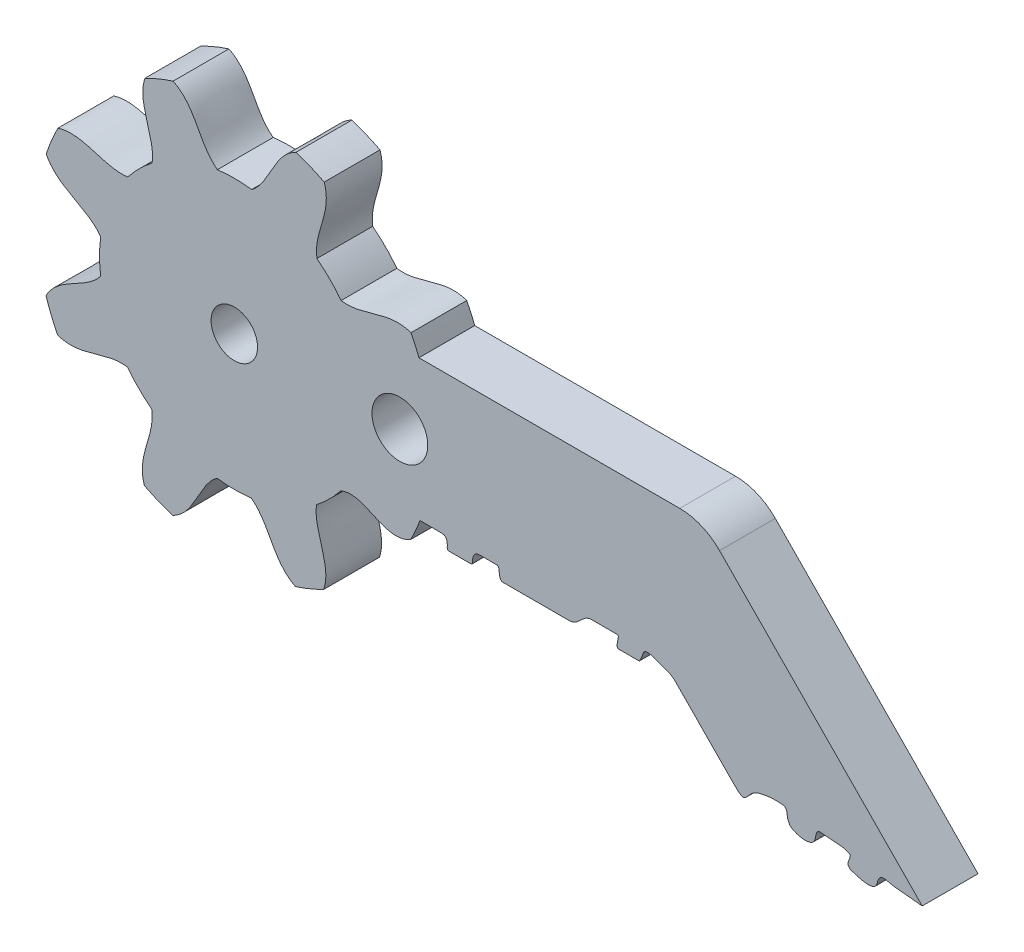
SolidWorks part; units mm, degrees
ref_plane "Plan de face" through (0, 0, 0) normal (0, 0, 1) x (1, 0, 0)
ref_plane "Plan de dessus" through (0, 0, 0) normal (0, 1, 0) x (1, 0, 0)
ref_plane "Plan de droite" through (0, 0, 0) normal (1, 0, 0) x (0, 0, -1)
sketch "Esquisse1" plane through (0, 0, 0) normal (0, 0, 1) x (1, 0, 0)
  line L0 (0.0131, -13.2918) -> (47.0131, -13.2918) construction
  line L1 (0, 0) -> (47, 0) construction
  line L2 (0, 0) -> (0, -20.3) construction
  line L3 (0, -20.3) -> (47, -20.3) construction
  line L4 (47, 0) -> (47, -20.3) construction
  line L5 (0, -10.15) -> (47, -10.15) construction
  line L6 (19.9298, -6.3) -> (35.218, -6.3)
  line L7 (47, -18.3) -> (35.218, -6.3)
  line L8 (10, -10.15) -> (5.9398, -0.3043) construction
  line L9 (33.7315, -14.492) -> (37.5973, -18.4293) construction
  line L10 (21.5121, -14.5) -> (22.7443, -14.5)
  line L11 (30.5976, -13.853) -> (29.2237, -13.853)
  line L12 (20.9504, -13.853) -> (19.9855, -13.853)
  line L13 (24.1135, -13.853) -> (23.1796, -13.853)
  line L14 (30.6788, -14.5) -> (31.7806, -14.5)
  line L15 (24.4805, -14.5) -> (28.0118, -14.5)
  line L16 (37.5973, -18.4293) -> (47, -18.3) construction
  line L17 (38.2306, -17.4342) -> (47, -18.3) construction
  line L18 (33.7315, -14.492) -> (36.7849, -17.6019)
  line L19 (45.6312, -18.1649) -> (47, -18.3)
  circle A0 centre (10, -10.15) radius 1.25
  circle A1 centre (18.7, -10.15) radius 1.25 construction
  circle A2 centre (10, -10.15) radius 7.25 construction
  circle A3 centre (10, -10.15) radius 10.65 construction
  arc A4 (5.1933, -0.6464) -> (6.7104, -0.0208) centre (10, -10.15) cw
  arc A5 (5.5762, -4.4061) -> (9.089, -2.9575) centre (10, -10.15) cw construction
  arc A6 (10.9334, -2.9603) -> (14.4417, -4.4199) centre (10, -10.15) cw construction
  arc A7 (13.3212, -0.0311) -> (14.8364, -0.6615) centre (10, -10.15) cw
  arc A8 (15.7439, -5.7262) -> (17.1925, -9.239) centre (10, -10.15) cw construction
  arc A9 (19.5036, -5.3433) -> (20.1292, -6.8604) centre (10, -10.15) cw construction
  arc A10 (17.1897, -11.0834) -> (15.7301, -14.5917) centre (10, -10.15) cw construction
  arc A11 (20.1189, -13.4712) -> (19.4885, -14.9864) centre (10, -10.15) cw construction
  arc A12 (14.4238, -15.8939) -> (10.911, -17.3425) centre (10, -10.15) cw construction
  arc A13 (14.8067, -19.6536) -> (13.2896, -20.2792) centre (10, -10.15) cw
  arc A14 (9.0666, -17.3397) -> (5.5583, -15.8801) centre (10, -10.15) cw construction
  arc A15 (6.6788, -20.2689) -> (5.1636, -19.6385) centre (10, -10.15) cw
  arc A16 (4.2561, -14.5738) -> (2.8075, -11.061) centre (10, -10.15) cw construction
  arc A17 (0.4964, -14.9567) -> (-0.1292, -13.4396) centre (10, -10.15) cw
  arc A18 (2.8103, -9.2166) -> (4.2699, -5.7083) centre (10, -10.15) cw construction
  arc A19 (-0.1189, -6.8288) -> (0.5115, -5.3136) centre (10, -10.15) cw
  arc A20 (5.5762, -4.4061) -> (4.2699, -5.7083) centre (10, -10.15) ccw
  arc A21 (2.8103, -9.2166) -> (2.8075, -11.061) centre (10, -10.15) ccw
  arc A22 (5.5583, -15.8801) -> (4.2561, -14.5738) centre (10, -10.15) cw
  arc A23 (9.0666, -17.3397) -> (10.911, -17.3425) centre (10, -10.15) ccw
  arc A24 (14.4238, -15.8939) -> (15.7301, -14.5917) centre (10, -10.15) ccw
  arc A25 (15.7439, -5.7262) -> (14.4417, -4.4199) centre (10, -10.15) ccw
  arc A26 (10.9334, -2.9603) -> (9.089, -2.9575) centre (10, -10.15) ccw
  arc A28 (19.5036, -5.3433) -> (19.9298, -6.3) centre (10, -10.15) cw
  arc A29 (31.9923, -14.0338) -> (31.7806, -14.5) centre (30.608, -13.6865) cw
  arc A30 (38.2306, -17.4342) -> (39.5821, -17.3425) centre (39.1417, -20.8578) cw
  arc A31 (19.9855, -13.853) -> (19.4885, -14.9864) centre (10, -10.15) cw
  spline S0 degree 3 poles (5.1933, -0.6464) (4.7495, -1.978) (5.7637, -3.1194) (5.5762, -4.4061) knots 0 0 0 0 1 1 1 1
  spline S1 degree 3 poles (6.7104, -0.0208) (7.9639, -0.6524) (8.049, -2.1769) (9.089, -2.9575) knots 0 0 0 0 1 1 1 1
  spline S2 degree 3 poles (13.3212, -0.0311) (12.0658, -0.6588) (11.9759, -2.1831) (10.9334, -2.9603) knots 0 0 0 0 1 1 1 1
  spline S3 degree 3 poles (14.8364, -0.6615) (15.276, -1.9945) (14.2583, -3.1327) (14.4417, -4.4199) knots 0 0 0 0 1 1 1 1
  spline S4 degree 3 poles (19.5036, -5.3433) (18.172, -4.8995) (17.0306, -5.9137) (15.7439, -5.7262) knots 0 0 0 0 1 1 1 1
  spline S5 degree 3 poles (20.1292, -6.8604) (19.4976, -8.1139) (17.9731, -8.199) (17.1925, -9.239) knots 0 0 0 0 1 1 1 1 construction
  spline S6 degree 3 poles (20.1189, -13.4712) (19.4912, -12.2158) (17.9669, -12.1259) (17.1897, -11.0834) knots 0 0 0 0 1 1 1 1 construction
  spline S7 degree 3 poles (19.4885, -14.9864) (18.0933, -15.8097) (17.0296, -14.0663) (15.7301, -14.5917) knots 0 0 0 0 1 1 1 1
  spline S8 degree 3 poles (14.8067, -19.6536) (15.2505, -18.322) (14.2363, -17.1806) (14.4238, -15.8939) knots 0 0 0 0 1 1 1 1
  spline S9 degree 3 poles (13.2896, -20.2792) (12.0361, -19.6476) (11.951, -18.1231) (10.911, -17.3425) knots 0 0 0 0 1 1 1 1
  spline S10 degree 3 poles (6.6788, -20.2689) (7.9342, -19.6412) (8.0241, -18.1169) (9.0666, -17.3397) knots 0 0 0 0 1 1 1 1
  spline S11 degree 3 poles (5.1636, -19.6385) (4.724, -18.3055) (5.7417, -17.1673) (5.5583, -15.8801) knots 0 0 0 0 1 1 1 1
  spline S12 degree 3 poles (0.4964, -14.9567) (1.828, -15.4005) (2.9694, -14.3863) (4.2561, -14.5738) knots 0 0 0 0 1 1 1 1
  spline S13 degree 3 poles (-0.1292, -13.4396) (0.5024, -12.1861) (2.0269, -12.101) (2.8075, -11.061) knots 0 0 0 0 1 1 1 1
  spline S14 degree 3 poles (-0.1189, -6.8288) (0.5088, -8.0842) (2.0331, -8.1741) (2.8103, -9.2166) knots 0 0 0 0 1 1 1 1
  spline S15 degree 3 poles (0.5115, -5.3136) (1.8445, -4.874) (2.9827, -5.8917) (4.2699, -5.7083) knots 0 0 0 0 1 1 1 1
  spline S16 degree 3 poles (33.7315, -14.492) (33.5145, -14.271) (33.0572, -14.1306) (32.0694, -13.7265) (31.9923, -14.0338) knots 0 0 0 0 0.472739 1 1 1 1
  spline S17 degree 3 poles (30.6788, -14.5) (30.5669, -14.5) (30.5909, -14.1849) (30.6968, -13.853) (30.5976, -13.853) knots 0 0 0 0 0.473984 1 1 1 1
  spline S18 degree 3 poles (29.2237, -13.853) (28.6964, -13.853) (28.5439, -14.5) (28.0118, -14.5) knots 0 0 0 0 1 1 1 1
  spline S19 degree 3 poles (24.4805, -14.5) (24.1191, -14.5111) (24.3591, -13.853) (24.1135, -13.853) knots 0 0 0 0 0.869022 0.869022 0.869022 0.869022
  spline S20 degree 3 poles (23.1796, -13.853) (22.9921, -13.853) (22.7705, -14.0665) (22.823, -14.5) (22.7443, -14.5) knots 0 0 0 0 0.61315 1 1 1 1
  spline S21 degree 3 poles (21.5121, -14.5) (21.4424, -14.5) (21.4715, -14.1754) (21.3884, -13.8364) (21.143, -13.853) (20.9504, -13.853) knots 0 0 0 0 0.15203 0.482763 1 1 1 1
  spline S22 degree 3 poles (36.7849, -17.6019) (37.2105, -18.0354) (37.5058, -18.1951) (37.7952, -17.5501) (38.2306, -17.4342) knots 0 0 0 0 0.460711 1 1 1 1
  spline S23 degree 3 poles (39.5821, -17.3425) (39.8217, -17.522) (39.6553, -17.7637) (39.8443, -18.0118) knots 0 0 0 0 1 1 1 1
  spline S24 degree 3 poles (39.8443, -18.0118) (39.9046, -18.3138) (41.4267, -18.7184) (41.2436, -17.6732) (41.4666, -17.6019) knots 0 0 0 0 0.70566 1 1 1 1
  spline S25 degree 3 poles (41.4666, -17.6019) (41.5041, -17.5899) (42.5058, -17.6938) (42.7995, -17.689) (43.0781, -17.8132) knots 0 0 0 0 0.477701 1 1 1 1
  spline S26 degree 3 poles (43.0781, -17.8132) (43.2331, -17.8822) (42.8688, -18.3192) (43.0875, -18.4922) (43.1472, -18.5509) knots 0 0 0 0 0.680949 1 1 1 1
  spline S27 degree 3 poles (43.1472, -18.5509) (43.0975, -18.5021) (43.7309, -18.7883) (44.5072, -18.79) (44.5748, -18.4531) knots 0 0 0 0 0.494583 1 1 1 1
  spline S28 degree 3 poles (44.5748, -18.4531) (44.6098, -18.2781) (44.8106, -17.8968) (45.2052, -18.1228) (45.6312, -18.1649) knots 0 0 0 0 0.363922 1 1 1 1
  point P88 (10, -10.15)
  dimension "D4" = 2.5
  dimension "D5" = 2.5
  dimension "D6" = 37
  dimension "D7" = 6.2
  dimension "D10" = 14.5
  dimension "D11" = 21.3
  dimension "D12" = 8
  dimension "D13" = 44.475
  dimension "D1" = 47
  dimension "D2" = 20.3
  dimension "D3" = 47
  dimension "D8" = 2
  dimension "D9" = 12
  dimension "D14" = 6.8
  dimension "D15" = 8.2
extrude "Boss.-Extru.1" add sketch "Esquisse1" along normal blind 3
fillet "Congé1" radius 3 1 edges at (35.218, -6.3, 1.5)
sketch "Esquisse2" plane through (0, 0, 0) normal (0, 0, -1) x (-1, 0, 0)
  circle A0 centre (-18.9044, -10.1416) radius 1.5
extrude "Enlèv. mat.-Extru.1" cut sketch "Esquisse2" against normal blind 10
